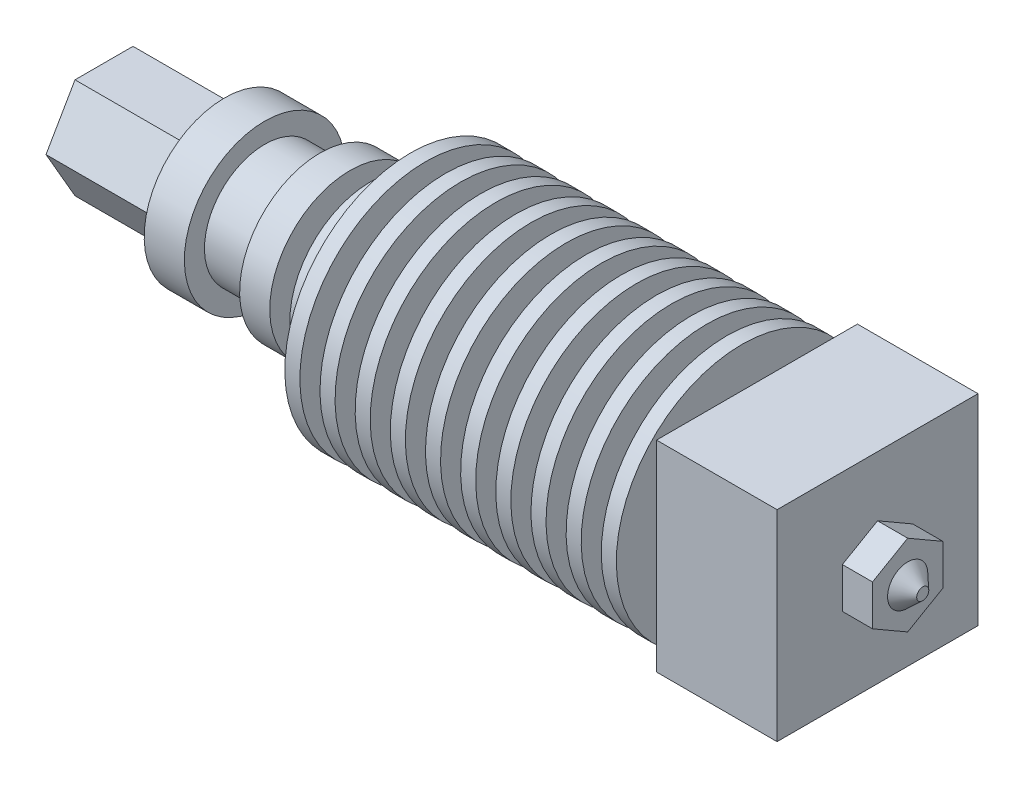
SolidWorks part; units mm, degrees
ref_plane "前基準面" through (0, 0, 0) normal (0, 0, 1) x (1, 0, 0)
ref_plane "上基準面" through (0, 0, 0) normal (0, 1, 0) x (1, 0, 0)
ref_plane "右基準面" through (0, 0, 0) normal (1, 0, 0) x (0, 0, -1)
sketch "草圖1" plane through (0, 0, 0) normal (0, 0, 1) x (1, 0, 0)
  line L0 (0, 0) -> (-51.5, 0)
  line L1 (0, 0) -> (0, 12.5)
  line L2 (0, 12.5) -> (-1.5, 12.5)
  line L3 (-1.5, 12.5) -> (-1.5, 7.5)
  line L4 (-1.5, 7.5) -> (-3.5, 7.5)
  line L5 (-3.5, 7.5) -> (-3.5, 12.5)
  line L6 (-3.5, 7.5) -> (-3.5, 12.5)
  line L7 (-5, 12.5) -> (-5, 7.5)
  line L8 (-5, 7.5) -> (-7, 7.5)
  line L9 (-7, 7.5) -> (-7, 12.5)
  line L10 (-3.5, 12.5) -> (-5, 12.5)
  line L11 (-7, 7.5) -> (-7, 12.5)
  line L12 (-8.5, 12.5) -> (-8.5, 7.5)
  line L13 (-8.5, 7.5) -> (-10.5, 7.5)
  line L14 (-10.5, 7.5) -> (-10.5, 12.5)
  line L15 (-7, 12.5) -> (-8.5, 12.5)
  line L16 (-10.5, 7.5) -> (-10.5, 12.5)
  line L17 (-12, 12.5) -> (-12, 7.5)
  line L18 (-12, 7.5) -> (-14, 7.5)
  line L19 (-14, 7.5) -> (-14, 12.5)
  line L20 (-10.5, 12.5) -> (-12, 12.5)
  line L21 (-14, 7.5) -> (-14, 12.5)
  line L22 (-15.5, 12.5) -> (-15.5, 7.5)
  line L23 (-15.5, 7.5) -> (-17.5, 7.5)
  line L24 (-17.5, 7.5) -> (-17.5, 12.5)
  line L25 (-14, 12.5) -> (-15.5, 12.5)
  line L26 (-17.5, 7.5) -> (-17.5, 12.5)
  line L27 (-19, 12.5) -> (-19, 7.5)
  line L28 (-19, 7.5) -> (-21, 7.5)
  line L29 (-21, 7.5) -> (-21, 12.5)
  line L30 (-17.5, 12.5) -> (-19, 12.5)
  line L31 (-21, 7.5) -> (-21, 12.5)
  line L32 (-22.5, 12.5) -> (-22.5, 7.5)
  line L33 (-22.5, 7.5) -> (-24.5, 7.5)
  line L34 (-24.5, 7.5) -> (-24.5, 12.5)
  line L35 (-21, 12.5) -> (-22.5, 12.5)
  line L36 (-24.5, 7.5) -> (-24.5, 12.5)
  line L37 (-26, 12.5) -> (-26, 7.5)
  line L38 (-26, 7.5) -> (-28, 7.5)
  line L39 (-28, 7.5) -> (-28, 12.5)
  line L40 (-24.5, 12.5) -> (-26, 12.5)
  line L41 (-28, 7.5) -> (-28, 12.5)
  line L42 (-29.5, 12.5) -> (-29.5, 7.5)
  line L43 (-29.5, 7.5) -> (-31.5, 7.5)
  line L44 (-31.5, 7.5) -> (-31.5, 12.5)
  line L45 (-28, 12.5) -> (-29.5, 12.5)
  line L46 (-31.5, 7.5) -> (-31.5, 12.5)
  line L47 (-33, 12.5) -> (-33, 7.5)
  line L48 (-35.5, 7.5) -> (-33, 7.5)
  line L49 (-35.5, 7.5) -> (-35.5, 8)
  line L50 (-31.5, 12.5) -> (-33, 12.5)
  line L51 (-35, 7.5) -> (-35, 12.5) [skipped]
  line L52 (-35.5, 8) -> (-37, 8)
  line L53 (-37, 8) -> (-37, 4.5)
  line L54 (-37, 4.5) -> (-39, 4.5)
  line L55 (-39, 4.5) -> (-39, 8)
  line L56 (-39, 8) -> (-42, 8)
  line L57 (-42, 8) -> (-42, 6)
  line L58 (-42, 6) -> (-47.5, 6)
  line L59 (-47.5, 6) -> (-47.5, 8)
  line L60 (-47.5, 8) -> (-51.5, 8)
  line L61 (-51.5, 8) -> (-51.5, 0)
  line L62 (-33, 7.5) -> (-35, 7.5) [skipped]
  dimension "D1" = 12.5
  dimension "D2" = 7.5
  dimension "D3" = 1.5
  dimension "D4" = 2
  dimension "D5" = 5
  dimension "D7" = 2
  dimension "D8" = 8
  dimension "D9" = 3
  dimension "D10" = 4
  dimension "D11" = 8
  dimension "D12" = 6
  dimension "D13" = 8
  dimension "D14" = 4.5
  dimension "D15" = 1.5
  dimension "D16" = 5.5
  dimension "D17" = 51.5
  dimension "D18" = 9
  dimension "D19" = 2.5
  dimension "D6" = 10
revolve "旋轉1" add sketch "草圖1" angle 360 about L0
sketch "草圖2" plane through (0, 0, 0) normal (1, 0, 0) x (0, 0, -1)
  circle A0 centre (0, 0) radius 3
  dimension "D1" = 6
extrude "填料-伸長1" add sketch "草圖2" along normal blind 1.5
sketch "草圖3" plane through (1.5, 0, 0) normal (1, 0, 0) x (0, 0, -1)
  line L1 (10, 10) -> (-10, 10)
  line L2 (10, 10) -> (10, -10)
  line L3 (10, -10) -> (-10, -10)
  line L4 (-10, 10) -> (-10, -10)
  point P4 (0, 10)
  point P6 (-10, 0)
  dimension "D1" = 20
  dimension "D2" = 20
extrude "填料-伸長2" add sketch "草圖3" along normal blind 12
sketch "草圖4" plane through (13.5, 0, 0) normal (1, 0, 0) x (0, 0, -1)
  line L1 (0, 4.0415) -> (-3.5, 2.0207)
  line L2 (-3.5, 2.0207) -> (-3.5, -2.0207)
  line L3 (-3.5, -2.0207) -> (0, -4.0415)
  line L4 (0, -4.0415) -> (3.5, -2.0207)
  line L5 (3.5, -2.0207) -> (3.5, 2.0207)
  line L6 (3.5, 2.0207) -> (0, 4.0415)
  circle A0 centre (0, 0) radius 3.5 construction
  dimension "D1" = 7
extrude "填料-伸長3" add sketch "草圖4" along normal blind 3
sketch "草圖6" plane through (0, 0, 0) normal (0, 0, 1) x (1, 0, 0)
  line L0 (16.5, 0) -> (18, 0)
  line L1 (16.5, 2.0207) -> (16.5, -2.0207) construction
  line L2 (18, 0) -> (18, 0.6)
  line L3 (18, 0.6) -> (16.5, 2)
  line L4 (16.5, 4.0415) -> (16.5, 2.0207) construction
  line L5 (16.5, 2) -> (16.5, 0)
  dimension "D1" = 2
  dimension "D2" = 1.5
  dimension "D3" = 0.6
revolve "旋轉2" add sketch "草圖6" angle 360 about L0
sketch "草圖7" plane through (-51.5, 0, 0) normal (-1, 0, 0) x (0, 0, 1)
  line L1 (-5.7735, 0) -> (-2.8868, -5)
  line L2 (-2.8868, -5) -> (2.8868, -5)
  line L3 (2.8868, -5) -> (5.7735, 0)
  line L4 (5.7735, 0) -> (2.8868, 5)
  line L5 (2.8868, 5) -> (-2.8868, 5)
  line L6 (-2.8868, 5) -> (-5.7735, 0)
  circle A0 centre (0, 0) radius 5 construction
  dimension "D1" = 10
extrude "填料-伸長4" add sketch "草圖7" along normal blind 12
sketch "草圖8" plane through (18, 0, 0) normal (1, 0, 0) x (0, 0, -1)
  circle A0 centre (0, 0) radius 100
  dimension "D1" = 200
extrude "填料-伸長5" [suppressed] add sketch "草圖8" along normal blind 1
